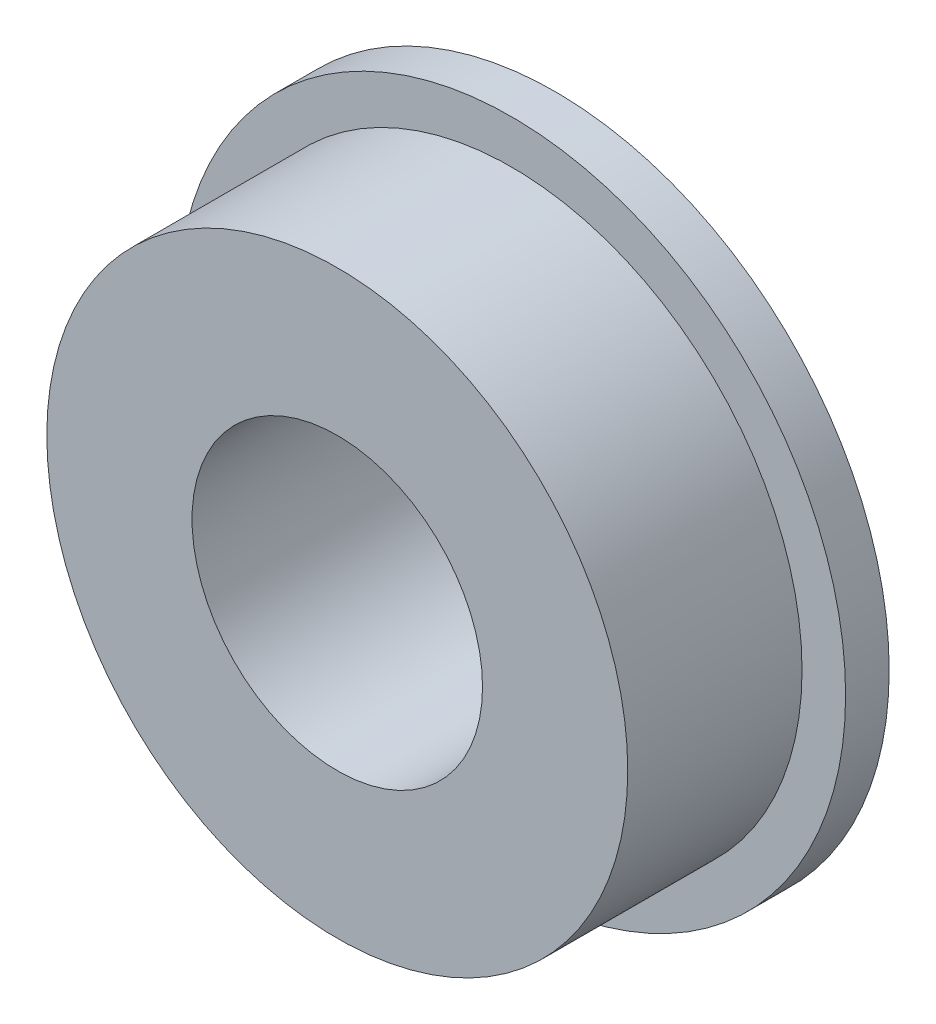
SolidWorks part; units mm, degrees
ref_plane "前视基准面" through (0, 0, 0) normal (0, 0, 1) x (1, 0, 0)
ref_plane "上视基准面" through (0, 0, 0) normal (0, 1, 0) x (1, 0, 0)
ref_plane "右视基准面" through (0, 0, 0) normal (1, 0, 0) x (0, 0, -1)
sketch "草图1" plane through (0, 0, 0) normal (0, 0, 1) x (1, 0, 0)
  circle A0 centre (0, 0) radius 4.6
  dimension "D1" = 9.2
extrude "凸台-拉伸1" add sketch "草图1" along normal blind 0.6
sketch "草图2" plane through (0, 0, 0.6) normal (0, 0, 1) x (1, 0, 0)
  circle A0 centre (0, 0) radius 4
  dimension "D1" = 8
extrude "凸台-拉伸2" add sketch "草图2" along normal blind 2.4
sketch "草图3" plane through (0, 0, 3) normal (0, 0, 1) x (1, 0, 0)
  circle A0 centre (0, 0) radius 2
  dimension "D1" = 4
extrude "切除-拉伸1" cut sketch "草图3" against normal through all
